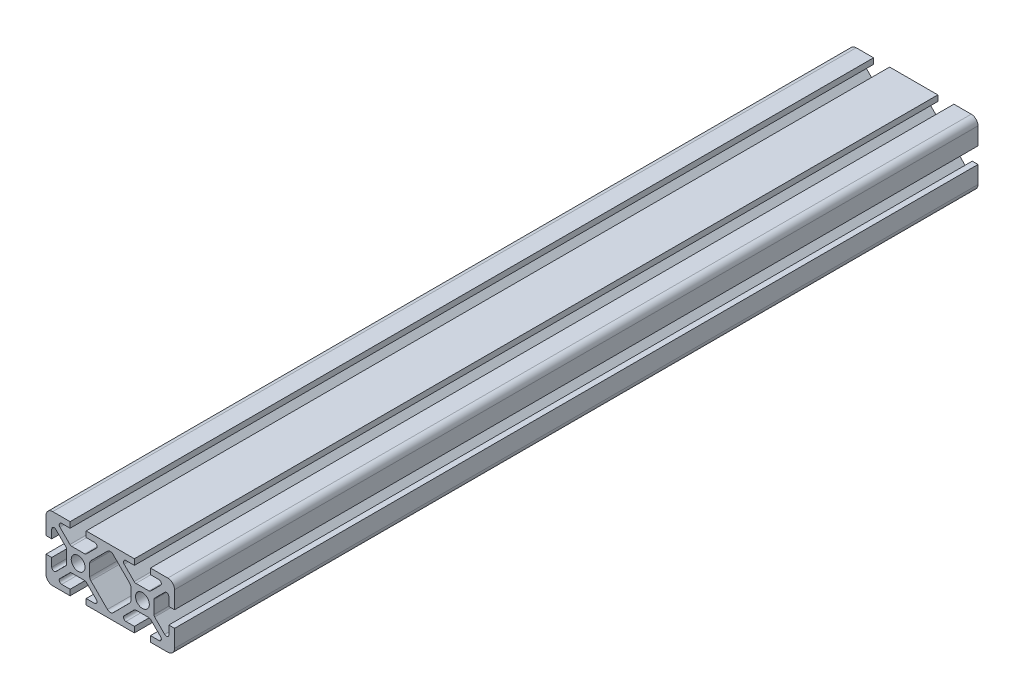
SolidWorks part; units mm, degrees
ref_plane "Front Plane" through (0, 0, 0) normal (0, 0, 1) x (1, 0, 0)
ref_plane "Top Plane" through (0, 0, 0) normal (0, 1, 0) x (1, 0, 0)
ref_plane "Right Plane" through (0, 0, 0) normal (1, 0, 0) x (0, 0, -1)
sketch "Sketch1" plane through (0, 0, 0) normal (0, 0, 1) x (1, 0, 0)
  line L0 (10, 10) -> (10, -10) construction
  line L1 (-20, 0) -> (20, 0) construction
  line L2 (12.5, -10) -> (20, -10)
  line L3 (20, -10) -> (20, -2.5)
  line L4 (12.5, -10) -> (12.5, -8.2134)
  line L5 (12.5, -8.2134) -> (16.95, -8.2134)
  line L6 (16.95, -8.2134) -> (12.3366, -3.6)
  line L7 (10, 0) -> (20, -10) construction
  line L8 (20, -2.5) -> (18.2134, -2.5)
  line L9 (18.2134, -2.5) -> (18.2134, -6.95)
  line L10 (18.2134, -6.95) -> (13.6, -2.3366)
  line L11 (15.9067, -4.6433) -> (14.6433, -5.9067) construction
  line L12 (0, 10) -> (0, -10) construction
  line L13 (0, -10) -> (-20, -10) construction
  line L14 (-10, 10) -> (10, 10) construction
  line L15 (20, 2.5) -> (20, -2.5) construction
  circle A0 centre (10, 0) radius 2.15
  arc A1 (15.5015, -8.2134) -> (15.9257, -7.1891) centre (15.5015, -7.6134) ccw construction
  point P8 (10, -3.6)
  point P16 (15.275, -5.275)
  point P30 (20, 0)
  dimension "Center Hole Diameter" = 4.3
  dimension "D3" = 0.6
  dimension "Rail Width" = 20
  dimension "T-Slot Width" = 5
  dimension "Slot Depth" = 6.4
  dimension "Rail Height" = 40
  dimension "Inner Slot Width" = 13.9
  dimension "Hole Spacing" = 20
sketch "Sketch2" plane through (0, 0, 0) normal (1, 0, 0) x (0, 0, -1)
  line L0 (-125, -10) -> (125, -10) construction
  line L1 (-85, 0) -> (85, 0) construction
  point P6 (-85, 0)
  point P8 (85, 0)
  dimension "Length" = 250
  dimension "D1" = 40
sketch "Sketch3" plane through (0, 0, 0) normal (0, 0, 1) x (1, 0, 0)
  line L0 (12.5, -10) -> (17.9, -10)
  line L1 (12.5, -10) -> (20, -10) construction
  line L2 (12.5, -10) -> (12.5, -8.2134) construction
  line L3 (12.5, -8.2134) -> (16.95, -8.2134) construction
  line L4 (12.5, -8.2134) -> (12.5, -10)
  line L5 (12.5, -8.2134) -> (16.95, -8.2134)
  line L6 (10, -3.6) -> (12.3366, -3.6)
  line L7 (16.95, -8.2134) -> (12.3366, -3.6) construction
  line L8 (12.3366, -3.6) -> (16.95, -8.2134)
  line L9 (20, -10) -> (20, -2.5) construction
  line L10 (18.2134, -6.95) -> (13.6, -2.3366) construction
  line L11 (18.2134, -2.5) -> (18.2134, -6.95) construction
  line L12 (18.2134, -6.95) -> (18.2134, -2.5)
  line L13 (20, -2.5) -> (18.2134, -2.5) construction
  line L14 (18.2134, -2.5) -> (20, -2.5)
  line L15 (20, -2.5) -> (20, -7.9)
  line L16 (18.2134, -6.95) -> (13.6, -2.3366)
  line L17 (13.6, 0) -> (13.6, -2.3366)
  line L18 (-20, 0) -> (20, 0) construction
  line L19 (10, -3.6) -> (10, -2.15)
  line L20 (10, 10) -> (10, -10) construction
  line L21 (13.6, 0) -> (12.15, 0)
  arc A5 (17.9, -10) -> (20, -7.9) centre (17.9, -7.9) ccw
  circle A10 centre (10, 0) radius 2.15 construction
  arc A11 (10, -2.15) -> (12.15, 0) centre (10, 0) ccw
  dimension "D1" = 2.1
extrude "Boss-Extrude1" add sketch "Sketch3" along normal mid plane 250
sketch "Sketch4" plane through (0, 0, 0) normal (0, 0, 1) x (1, 0, 0)
  line L0 (10, -3.6) -> (7.6634, -3.6)
  line L4 (7.6634, -3.6) -> (3.05, -8.2134)
  line L5 (3.05, -8.2134) -> (7.5, -8.2134)
  line L6 (7.5, -8.2134) -> (7.5, -10)
  line L18 (7.5, -10) -> (0, -10)
  line L19 (12.5, -10) -> (12.5, -8.2134) construction
  line L20 (12.5, -8.2134) -> (16.95, -8.2134) construction
  line L21 (10, -3.6) -> (12.3366, -3.6) construction
  line L22 (16.95, -8.2134) -> (12.3366, -3.6) construction
  line L23 (0, -8.7366) -> (6.4, -2.3366)
  line L24 (0, 10) -> (0, -10) construction
  line L25 (6.4, -2.3366) -> (6.4, 0)
  line L26 (-20, 0) -> (20, 0) construction
  line L27 (6.4, 0) -> (7.85, 0)
  line L28 (13.6, 0) -> (12.15, 0) construction
  line L29 (0, -8.7366) -> (0, -10)
  line L30 (10, -2.15) -> (10, -3.6)
  circle A4 centre (10, 0) radius 2.15 construction
  arc A5 (7.85, 0) -> (10, -2.15) centre (10, 0) ccw
extrude "Boss-Extrude2" add sketch "Sketch4" along normal mid plane 250
mirror "Mirror1" about plane through (0, 0, 0) normal (1, 0, 0) of bodies 137 134
mirror "Mirror2" about plane through (0, 0, 0) normal (0, 1, 0) of bodies 135
fillet "Fillet1" radius 0.75 24 edges at (-7.6634, -3.6, 0) (-12.3366, -3.6, 0) (12.3366, -3.6, 0) (7.6634, -3.6, 0) (-3.05, -8.2134, 0) (-18.2134, -6.95, 0) (-16.95, -8.2134, 0) (-13.6, -2.3366, 0) (-18.2134, 6.95, 0) (-16.95, 8.2134, 0) (-12.3366, 3.6, 0) (-7.6634, 3.6, 0) (-13.6, 2.3366, 0) (-3.05, 8.2134, 0) (3.05, 8.2134, 0) (13.6, -2.3366, 0) (18.2134, 6.95, 0) (13.6, 2.3366, 0) (7.6634, 3.6, 0) (12.3366, 3.6, 0) (16.95, 8.2134, 0) (18.2134, -6.95, 0) (16.95, -8.2134, 0) (3.05, -8.2134, 0)
fillet "Fillet2" radius 1.25 6 edges at (0, -8.7366, 0) (-6.4, -2.3366, 0) (0, 8.7366, 0) (-6.4, 2.3366, 0) (6.4, -2.3366, 0) (6.4, 2.3366, 0)
equation "\"D1@Sketch3\" = \"D3@Sketch1\" * 3.5"
equation "\"D1@Boss-Extrude1\" = \"Length@Sketch2\""
equation "\"D1@Boss-Extrude2\" = \"Length@Sketch2\""
equation "\"D1@Sketch2\"=\"Rail Height@Sketch1\""
